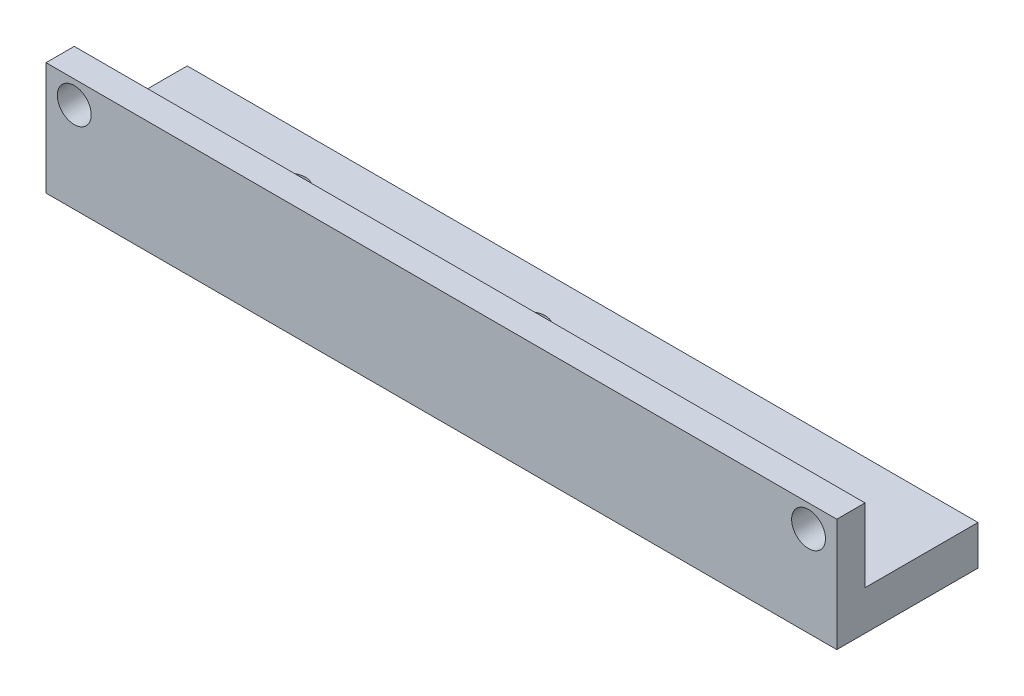
SolidWorks part; units mm, degrees
ref_plane "Front Plane" through (0, 0, 0) normal (0, 0, 1) x (1, 0, 0)
ref_plane "Top Plane" through (0, 0, 0) normal (0, 1, 0) x (1, 0, 0)
ref_plane "Right Plane" through (0, 0, 0) normal (1, 0, 0) x (0, 0, -1)
sketch "Sketch1" plane through (0, 0, 0) normal (0, 1, 0) x (1, 0, 0)
  line L1 (0, 0) -> (140, 0)
  line L2 (0, 0) -> (0, 25)
  line L3 (0, 25) -> (140, 25)
  line L4 (140, 0) -> (140, 25)
  dimension "D1" = 25
  dimension "D2" = 140
extrude "Boss-Extrude1" add sketch "Sketch1" along normal blind 20
sketch "Sketch2" plane through (0, 20, 0) normal (0, 1, 0) x (1, 0, 0)
  line L0 (140, 0) -> (140, 25) construction
  line L1 (0, 25) -> (140, 25)
  line L2 (0, 25) -> (0, 5)
  line L3 (0, 5) -> (140, 5)
  line L4 (140, 25) -> (140, 5)
  dimension "D1" = 20
extrude "Cut-Extrude1" cut sketch "Sketch2" against normal blind 15
sketch "Sketch3" plane through (0, 0, 0) normal (0, 0, 1) x (1, 0, 0)
  line L0 (0, 20) -> (140, 20) construction
  line L1 (140, 20) -> (140, 0) construction
  line L2 (0, 20) -> (0, 0) construction
  circle A0 centre (5, 14) radius 3
  circle A1 centre (135, 14) radius 3
  dimension "D1" = 6
  dimension "D2" = 6
  dimension "D3" = 6
  dimension "D4" = 5
  dimension "D5" = 5
  dimension "D6" = 6
extrude "Cut-Extrude2" cut sketch "Sketch3" against normal blind 15
sketch "Sketch4" plane through (0, 5, 0) normal (0, 1, 0) x (1, 0, 0)
  line L0 (140, 25) -> (0, 25) construction
  line L2 (140, 5) -> (140, 25) construction
  circle A0 centre (70, 15.4) radius 3
  circle A1 centre (27.5, 15.4) radius 3
  dimension "D1" = 6
  dimension "D2" = 9.6
  dimension "D3" = 70
  dimension "D4" = 6
  dimension "D5" = 9.6
  dimension "D6" = 42.5
extrude "Cut-Extrude3" cut sketch "Sketch4" against normal through all both and the other way through all
sketch "Sketch5" plane through (0, 0, -5) normal (0, 0, -1) x (-1, 0, 0)
  line L0 (0, 5) -> (0, 20) construction
  line L1 (-140, 20) -> (0, 20)
  line L2 (-140, 20) -> (-140, 18)
  line L3 (-140, 18) -> (0, 18)
  line L4 (0, 20) -> (0, 18)
  dimension "D1" = 2
extrude "Cut-Extrude4" cut sketch "Sketch5" against normal blind 15
sketch "Sketch7" plane through (0, 0, 0) normal (0, -1, 0) x (1, 0, 0)
  line L1 (140, 0) -> (0, 0)
  line L2 (140, 0) -> (140, -25)
  line L3 (140, -25) -> (0, -25)
  line L4 (0, 0) -> (0, -25)
extrude "Boss-Extrude2" add sketch "Sketch7" along normal blind 2
sketch "Sketch8" plane through (0, 0, -25) normal (0, 0, -1) x (-1, 0, 0)
  line L0 (-140, 5) -> (0, 5) construction
  line L1 (-74, 4) -> (-66, 4)
  line L2 (-74, 4) -> (-74, -1)
  line L3 (-74, -1) -> (-66, -1)
  line L4 (-66, 4) -> (-66, -1)
  line L5 (-140, 5) -> (-140, -2) construction
  line L7 (-31.5, 4) -> (-23.5, 4)
  line L8 (-31.5, 4) -> (-31.5, -1)
  line L9 (-31.5, -1) -> (-23.5, -1)
  line L10 (-23.5, 4) -> (-23.5, -1)
  line L11 (0, 5) -> (0, -2) construction
  dimension "D1" = 5
  dimension "D2" = 1
  dimension "D3" = 8
  dimension "D4" = 66
  dimension "D5" = 5
  dimension "D6" = 8
  dimension "D7" = 1
  dimension "D8" = 23.5
extrude "Cut-Extrude5" cut sketch "Sketch8" against normal blind 16
sketch "Sketch11" plane through (0, 5, 0) normal (0, 1, 0) x (1, 0, 0)
  circle A0 centre (27.5, 15.4) radius 3
  circle A1 centre (70, 15.4) radius 3
extrude "Cut-Extrude6" cut sketch "Sketch11" against normal through all both and the other way through all
